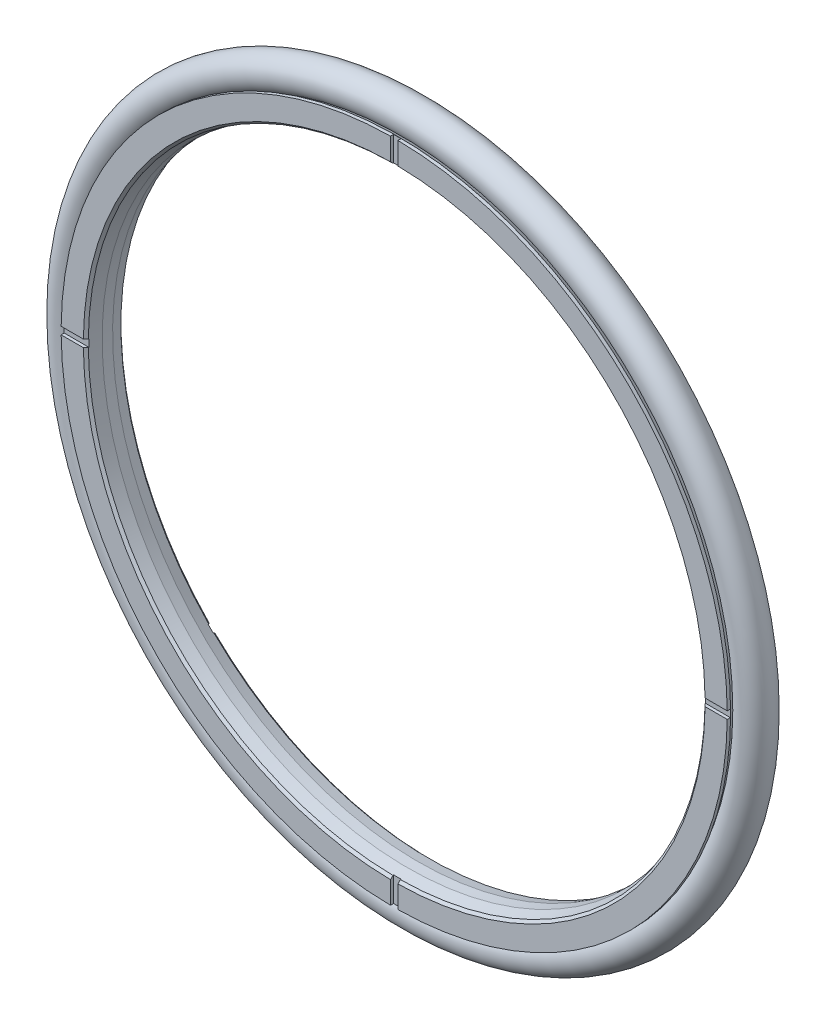
SolidWorks part; units mm, degrees
material "PTFE+NBR"
ref_plane "Front Plane" through (0, 0, 0) normal (0, 0, 1) x (1, 0, 0)
ref_plane "Top Plane" through (0, 0, 0) normal (0, 1, 0) x (1, 0, 0)
ref_plane "Right Plane" through (0, 0, 0) normal (1, 0, 0) x (0, 0, -1)
sketch "Sketch1" plane through (0, 0, 0) normal (1, 0, 0) x (0, 0, -1)
  line L0 (0, 0) -> (45.3047, 0) construction
  line L1 (0, 0) -> (0, 68.4894) construction
  line L2 (-3.05, 54.05) -> (-3.05, 50.45)
  line L3 (-0.85, 49.6) -> (0.85, 49.6)
  line L4 (3.05, 50.45) -> (3.05, 54.05)
  line L5 (-10.6026, 41.25) -> (12.2584, 41.25) construction
  line L6 (-3.05, 54.05) -> (-2.4995, 54.05)
  line L7 (3.05, 54.05) -> (2.4995, 54.05)
  line L8 (-2.65, 50.05) -> (-0.85, 49.6)
  line L9 (2.65, 50.05) -> (0.85, 49.6)
  line L10 (2.65, 50.05) -> (3.05, 50.45)
  line L11 (-3.05, 50.45) -> (-2.65, 50.05)
  arc A1 (-2.4995, 54.05) -> (2.4995, 54.05) centre (0, 56.5) ccw
  point P11 (-3.05, 50.15)
  point P15 (3.05, 50.15)
  dimension "D4" = 3.5
  dimension "D5" = 4.45
  dimension "D6" = 106
  dimension "D1" = 99.2
  dimension "D2" = 6.1
  dimension "D3" = 41.25
  dimension "D7" = 2.2
  dimension "D8" = 4
  dimension "D9" = 3.6
  dimension "D10" = 45
  dimension "D11" = 0.3
  dimension "D12" = 45
  dimension "D13" = 0.5505
  dimension "D14" = 100.9
  dimension "D15" = 108.1
revolve "Revolve1" add sketch "Sketch1" angle 360 about L0
sketch "Sketch3" plane through (0, 0, 3.05) normal (0, 0, 1) x (1, 0, 0)
  line L0 (0, 0) -> (0, 42.9701) construction
  line L2 (-0.6, 54.5677) -> (0.6, 54.5677)
  line L3 (-0.6, 54.5677) -> (-0.6, 0)
  line L4 (-0.6, 0) -> (0.6, 0)
  line L5 (0.6, 54.5677) -> (0.6, 0)
  dimension "D1" = 1.2
  dimension "D2" = 54.5677
extrude "Cut-Extrude1" cut sketch "Sketch3" against normal blind 0.5
sketch "Sketch4" plane through (0, 0, -3.05) normal (0, 0, -1) x (-1, 0, 0)
  line L0 (0, 0) -> (30.7412, 30.7412) construction
  line L1 (0, 0) -> (54.0122, 0) construction
  line L2 (0.4243, -0.4243) -> (-0.4243, 0.4243)
  line L3 (-0.4243, 0.4243) -> (46.107, 46.9556)
  line L4 (46.107, 46.9556) -> (46.9556, 46.107)
  line L5 (0.4243, -0.4243) -> (46.9556, 46.107)
  point P9 (46.5313, 46.5313)
  dimension "D1" = 45
  dimension "D2" = 1.2
  dimension "D3" = 65.8052
extrude "Cut-Extrude2" cut sketch "Sketch4" against normal blind 0.5
pattern_circular "CirPattern1" count 4 over 360 about axis through (0, 0, 0) along (0, 0, 1) of "Cut-Extrude1", "Cut-Extrude2"
sketch "Sketch2" plane through (0, 0, 0) normal (1, 0, 0) x (0, 0, -1)
  line L0 (0, 0) -> (20.1543, 0) construction
  circle A0 centre (0, 55.665) radius 2.665
  dimension "D1" = 5.33
  dimension "D2" = 106
revolve "Revolve2" add sketch "Sketch2" angle 360 about L0
